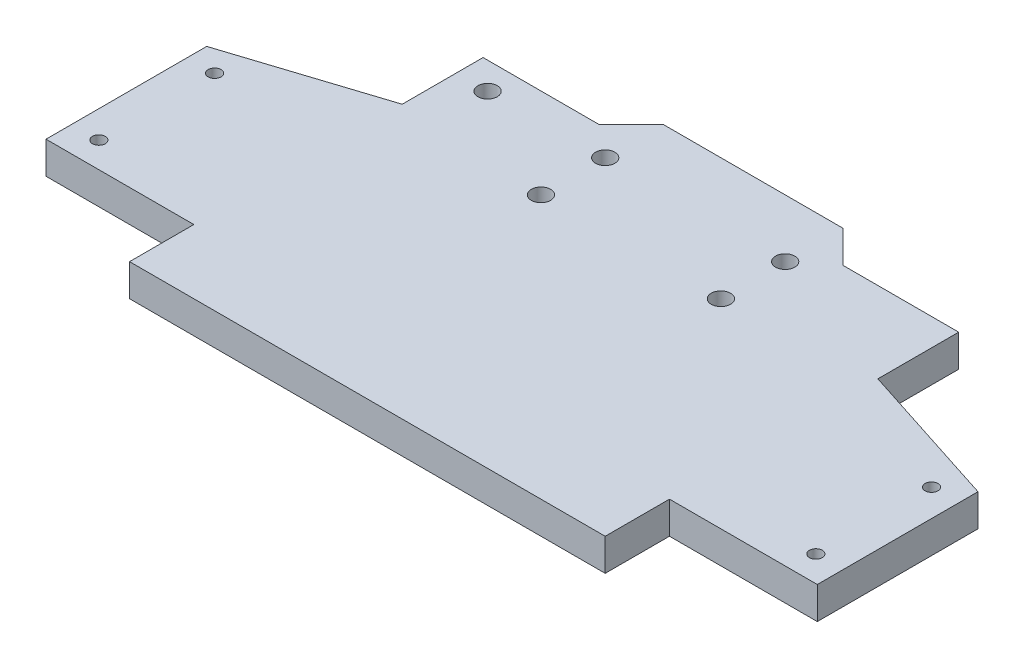
SolidWorks part; units mm, degrees
ref_plane "Front Plane" through (0, 0, 0) normal (0, 0, 1) x (1, 0, 0)
ref_plane "Top Plane" through (0, 0, 0) normal (0, 1, 0) x (1, 0, 0)
ref_plane "Right Plane" through (0, 0, 0) normal (1, 0, 0) x (0, 0, -1)
sketch "Sketch1" plane through (0, 0, 0) normal (0, 1, 0) x (1, 0, 0)
  line L24 (-28, -90) -> (-43, -105)
  line L26 (0, -90) -> (15, -105)
  line L27 (-28, -90) -> (-28, -105) construction
  line L28 (0, -90) -> (0, -105) construction
  line L32 (-28, -99) -> (0, -99) construction
  line L33 (0, -99) -> (-28, -109) construction
  line L34 (-28, -109) -> (0, -109) construction
  line L35 (0, -109) -> (-28, -99) construction
  line L36 (-28, -90) -> (0, -90)
  line L44 (-74, -115) -> (-74, -140)
  line L45 (-74, -140) -> (46, -140)
  line L46 (46, -140) -> (46, -115)
  line L48 (-74, -115) -> (-43, -105)
  line L49 (15, -105) -> (46, -115)
  line L50 (-69.77, -136) -> (-69.77, -118) construction
  line L51 (-14, -140) -> (-14, -90) construction
  circle A4 centre (-28, -99) radius 1.5
  circle A5 centre (0, -99) radius 1.5
  circle A6 centre (-28, -109) radius 1.5
  circle A7 centre (0, -109) radius 1.5
  circle A8 centre (-69.77, -136) radius 1
  circle A9 centre (-69.77, -118) radius 1
  circle A10 centre (41.77, -136) radius 1
  circle A11 centre (41.77, -118) radius 1
  dimension "D3" = 120
  dimension "D17" = 10
  dimension "D7" = 3
  dimension "D11" = 4
  dimension "D2" = 25
  dimension "D4" = 10
  dimension "D5" = 28
  dimension "D6" = 10
  dimension "D8" = 10
  dimension "D9" = 15
  dimension "D10" = 31
  dimension "D12" = 4.23
  dimension "D13" = 18
  dimension "D14" = 15
  dimension "D15" = 15
  dimension "D18" = 28
  dimension "D19" = 9
extrude "Boss-Extrude1" add sketch "Sketch1" along normal blind 3
sketch "Sketch2" plane through (0, 3, 0) normal (0, 1, 0) x (1, 0, 0)
  line L2 (-74, -115) -> (-74, -140)
  line L3 (-74, -140) -> (-51, -140)
  line L7 (46, -115) -> (46, -140)
  line L8 (46, -140) -> (23, -140)
  line L15 (-51, -107.5806) -> (-51, -140)
  line L16 (23, -107.5806) -> (23, -140)
  line L17 (-43, -105) -> (-74, -115) construction
  line L18 (-74, -115) -> (-51, -107.5806)
  line L19 (23, -107.5806) -> (46, -115)
  circle A0 centre (-69.77, -118) radius 1
  circle A1 centre (-69.77, -136) radius 1
  circle A2 centre (41.77, -118) radius 1
  circle A3 centre (41.77, -136) radius 1
  dimension "D1" = 23
  dimension "D2" = 23
extrude "Boss-Extrude2" add sketch "Sketch2" along normal blind 2
sketch "Sketch3" plane through (0, 3, 0) normal (0, 1, 0) x (1, 0, 0)
  line L0 (-74, -115) -> (-74, -140) construction
  line L1 (-51, -150) -> (23, -150)
  line L2 (-51, -150) -> (-51, -95)
  line L3 (-51, -95) -> (-33, -95)
  line L4 (23, -150) -> (23, -95)
  line L5 (46, -140) -> (46, -115) construction
  line L6 (-51, -140) -> (23, -140) construction
  line L7 (-33, -95) -> (-28, -90)
  line L8 (-28, -90) -> (-43, -105) construction
  line L9 (-28, -90) -> (0, -90)
  line L10 (0, -90) -> (5, -95)
  line L11 (15, -105) -> (0, -90) construction
  line L12 (5, -95) -> (23, -95)
  circle A0 centre (-28, -99) radius 1.5
  circle A1 centre (0, -99) radius 1.5
  circle A2 centre (0, -109) radius 1.5
  circle A3 centre (-28, -109) radius 1.5
  dimension "D1" = 23
  dimension "D2" = 23
  dimension "D3" = 55
  dimension "D4" = 10
extrude "Boss-Extrude4" add sketch "Sketch3" along normal blind 5 from surface at -3 starting at face at (-14, 0, 112.5)
sketch "Sketch4" plane through (0, 5, 0) normal (0, 1, 0) x (1, 0, 0)
  line L0 (-51, -95) -> (-51, -107.5806) construction
  line L1 (-33, -95) -> (-51, -95) construction
  circle A0 centre (-46.11, -99.19) radius 1.5
  dimension "D1" = 4.89
  dimension "D2" = 4.19
extrude "Cut-Extrude1" cut sketch "Sketch4" against normal through all
